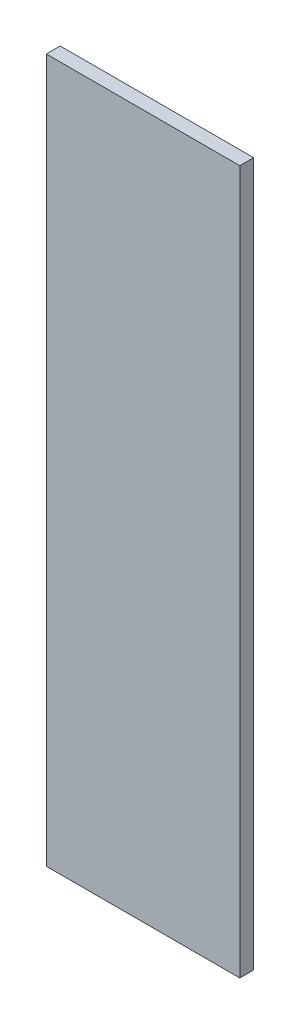
SolidWorks part; units mm, degrees
material "STYCAST 2850FT/Catalyst 23LV"
ref_plane "Front Plane" through (0, 0, 0) normal (0, 0, 1) x (1, 0, 0)
ref_plane "Top Plane" through (0, 0, 0) normal (0, 1, 0) x (1, 0, 0)
ref_plane "Right Plane" through (0, 0, 0) normal (1, 0, 0) x (0, 0, -1)
sketch "Sketch1" plane through (0, 0, 0) normal (0, 0, 1) x (1, 0, 0)
  line L1 (0, 0) -> (2.794, 0)
  line L2 (0, 0) -> (0, 10.16)
  line L3 (0, 10.16) -> (2.794, 10.16)
  line L4 (2.794, 0) -> (2.794, 10.16)
  dimension "D1" = 2.794
  dimension "D2" = 10.16
extrude "Boss-Extrude1" add sketch "Sketch1" along normal blind 0.2
